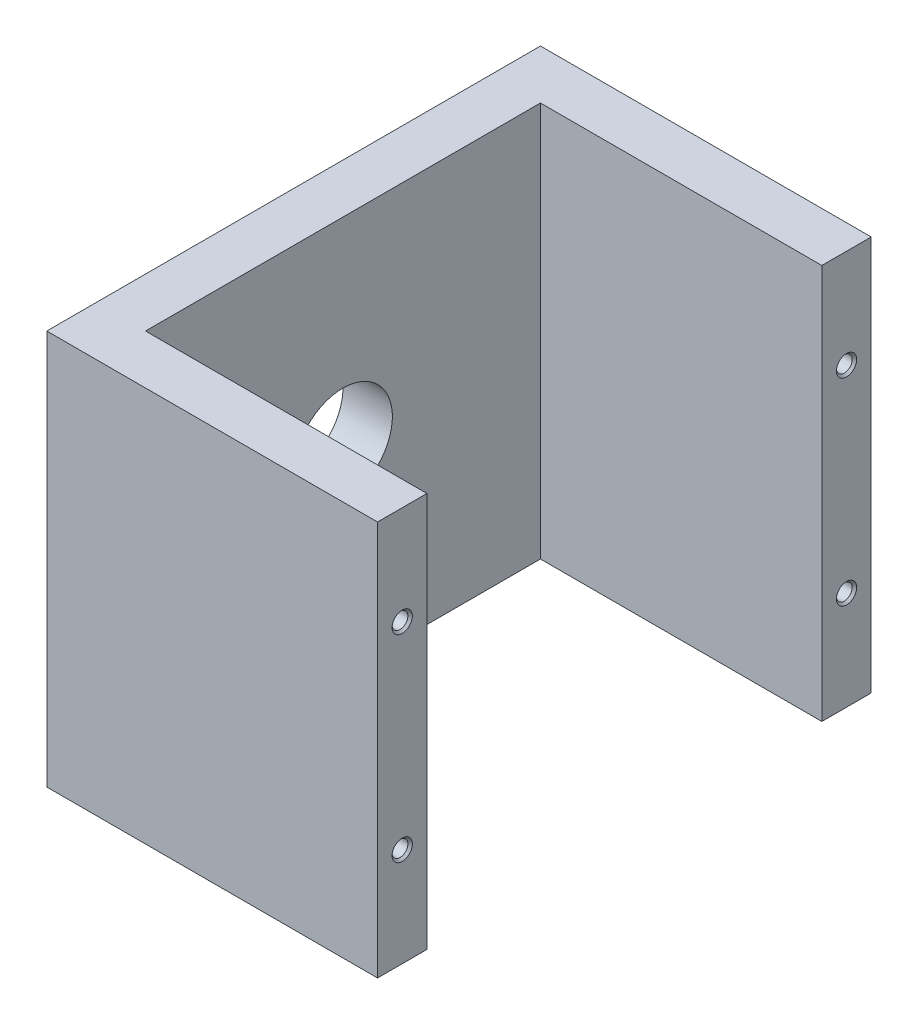
SolidWorks part; units mm, degrees
ref_plane "Front Plane" through (0, 0, 0) normal (0, 0, 1) x (1, 0, 0)
ref_plane "Top Plane" through (0, 0, 0) normal (0, 1, 0) x (1, 0, 0)
ref_plane "Right Plane" through (0, 0, 0) normal (1, 0, 0) x (0, 0, -1)
sketch "Sketch1" plane through (0, 0, 0) normal (0, 1, 0) x (1, 0, 0)
  line L0 (33.5, 0) -> (33.5, -5)
  line L7 (33.5, 0) -> (0, 0)
  line L9 (5, -45) -> (33.5, -45)
  line L10 (33.5, -45) -> (33.5, -50)
  line L16 (33.5, -5) -> (5, -5)
  line L17 (5, -5) -> (5, -45)
  line L19 (12, -25) -> (33.0104, -25) construction
  line L21 (33.5, -50) -> (0, -50)
  line L22 (0, -50) -> (0, 0)
  point P0 (0, 0)
  point P6 (0, 0)
  point P15 (33.5, -47.5)
  dimension "D1" = 5
  dimension "D2" = 5
  dimension "D3" = 28.5
  dimension "D4" = 22.5
  dimension "D5" = 33.5
extrude "Boss-Extrude1" add sketch "Sketch1" along normal blind 40
sketch "Sketch2" plane through (0, 0, 0) normal (-1, 0, 0) x (0, 0, 1)
  line L1 (0, 0) -> (50, 0) construction
  circle A0 centre (25, 20) radius 5
  point P8 (25, 20)
  dimension "D1" = 10
  dimension "D2" = 20
extrude "Cut-Extrude1" cut sketch "Sketch2" against normal up to next
sketch "Sketch18" plane through (33.5, 0, 0) normal (1, 0, 0) x (0, 0, -1)
  line L2 (-47.5, 40) -> (-47.5, 0) construction
  line L4 (-50, 40) -> (-45, 40) construction
  line L5 (-50, 0) -> (-45, 0) construction
  line L6 (-9.294, 15) -> (-4.0033, 15) construction
  line L7 (-25, 40) -> (-25, 0) construction
  line L8 (-45, 40) -> (-5, 40) construction
  line L9 (-45, 0) -> (-5, 0) construction
  point P1 (-47.5, 34.25)
  point P6 (-5.5393, 13.3787)
  point P13 (-47.5, -4.25)
  point P20 (-2.5, -4.25)
  point P21 (-2.5, 34.25)
  dimension "D1" = 5.75
sketch "Sketch19" plane through (33.5, 0, 0) normal (1, 0, 0) x (0, 0, -1)
  line L1 (-47.5, 40) -> (-47.5, 0) construction
  line L2 (-50, 40) -> (-45, 40) construction
  line L3 (-50, 0) -> (-45, 0) construction
  line L4 (-50, 20) -> (0, 20) construction
  line L5 (-50, 40) -> (-50, 0) construction
  line L6 (0, 40) -> (0, 0) construction
  line L7 (-2.5, 40) -> (-2.5, 0) construction
  line L8 (-5, 40) -> (0, 40) construction
  line L9 (-5, 0) -> (0, 0) construction
  circle A0 centre (-47.5, 30) radius 2
  circle A1 centre (-2.5, 30) radius 2
  circle A2 centre (-47.5, 10) radius 2
  circle A3 centre (-2.5, 10) radius 2
  dimension "D1" = 10
  dimension "D2" = 10
  dimension "D3" = 45
hole_wizard "M2 Tapped Hole2" positions "3DSketch1" profile "Sketch20" tap size "M2" standard "ISO"
sketch3d "3DSketch1"
  point P1 (33.5, 30, 47.5)
  point P4 (33.5, 10, 47.5)
  point P7 (33.5, 10, 2.5)
  point P10 (33.5, 30, 2.5)
sketch "Sketch20" plane through (33.5, 30, 47.5) normal (0, 1, 0) x (0, 0, -1)
  line L0 (0, 0) -> (0, 5.4807)
  line L1 (0, 5.4807) -> (0.8, 5)
  line L2 (0.8, 5) -> (0.8, 0.225)
  line L3 (0.8, 0.225) -> (1.025, 0)
  line L5 (1.025, 0) -> (0, 0)
  line L6 (-0.8, 0.225) -> (-1.025, 0) construction
  line L10 (0, 5.4807) -> (-0.8, 5) construction
  line L11 (0, -6.35) -> (0, 107.95) construction
  dimension "Tap Drill Dia." = 1.6
  dimension "Tap Drill Depth" = 5
  dimension "Near C'Sink Dia." = 2.05
  dimension "Near C'Sink Angle" = 90
  dimension "Drill Angle" = 118
cosmetic thread "Hole Thread1" parameters "D1"=5, "D2"=2
cosmetic thread "Hole Thread2" parameters "D1"=5, "D2"=2
cosmetic thread "Hole Thread3" parameters "D1"=5, "D2"=2
cosmetic thread "Hole Thread4" parameters "D1"=5, "D2"=2
